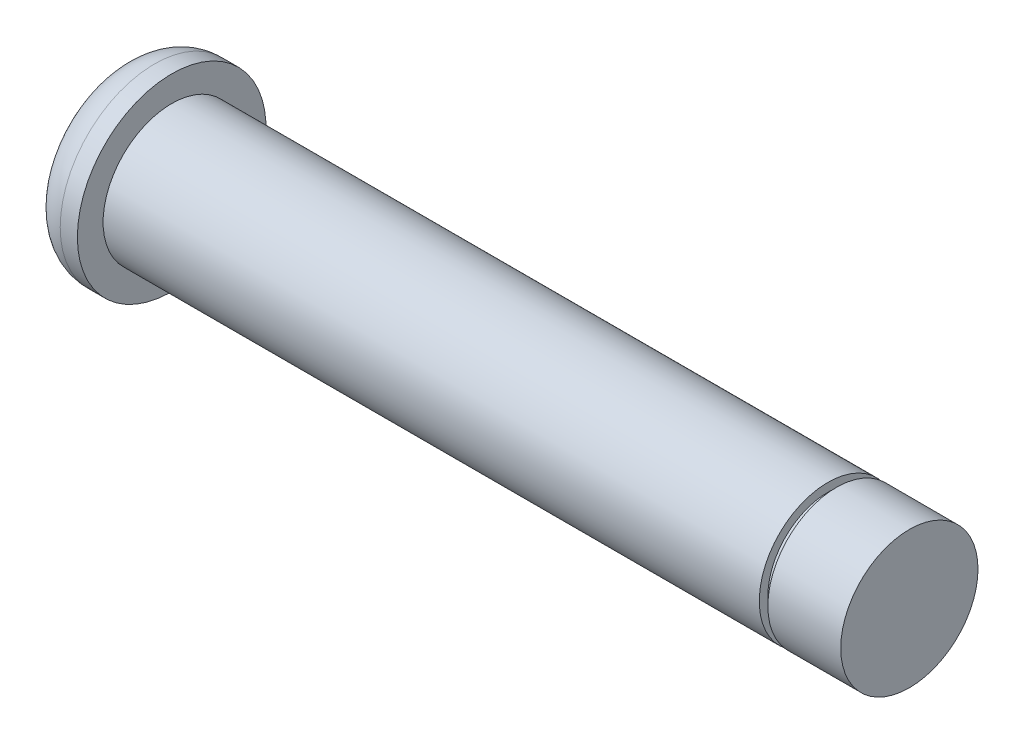
SolidWorks part; units mm, degrees
ref_plane "Front Plane" through (0, 0, 0) normal (0, 0, 1) x (1, 0, 0)
ref_plane "Top Plane" through (0, 0, 0) normal (0, 1, 0) x (1, 0, 0)
ref_plane "Right Plane" through (0, 0, 0) normal (1, 0, 0) x (0, 0, -1)
sketch "Sketch1" plane through (0, 0, 0) normal (1, 0, 0) x (0, 0, -1)
  circle A0 centre (0, 0) radius 4
  dimension "D1" = 8
extrude "Boss-Extrude1" add sketch "Sketch1" along normal blind 43
sketch "Sketch2" plane through (0, 0, 0) normal (-1, 0, 0) x (0, 0, 1)
  circle A0 centre (0, 0) radius 5.5
  dimension "D1" = 11
extrude "Boss-Extrude2" add sketch "Sketch2" along normal blind 3
fillet "Fillet1" radius 2 1 edges at (-3, 0, 5.5)
sketch "Sketch3" plane through (0, 0, 0) normal (0, 0, 1) x (1, 0, 0)
  line L0 (43, 4) -> (0, 4) construction
  line L1 (38.25, 4.5) -> (38.75, 4.5)
  line L2 (38.25, 4.5) -> (38.25, 3.5)
  line L3 (38.25, 3.5) -> (38.75, 3.5)
  line L4 (38.75, 4.5) -> (38.75, 3.5)
  line L5 (38.25, 4.5) -> (38.75, 3.5) construction
  line L6 (38.25, 3.5) -> (38.75, 4.5) construction
  line L7 (0, 0) -> (43, 0) construction
  line L8 (0, -4) -> (0, 4) construction
  line L9 (43, -4) -> (43, 4) construction
  point P0 (38.5, 4)
  dimension "D1" = 0.5
  dimension "D2" = 1
  dimension "D3" = 38.5
revolve "Cut-Revolve1" cut sketch "Sketch3" angle 360 about L7
